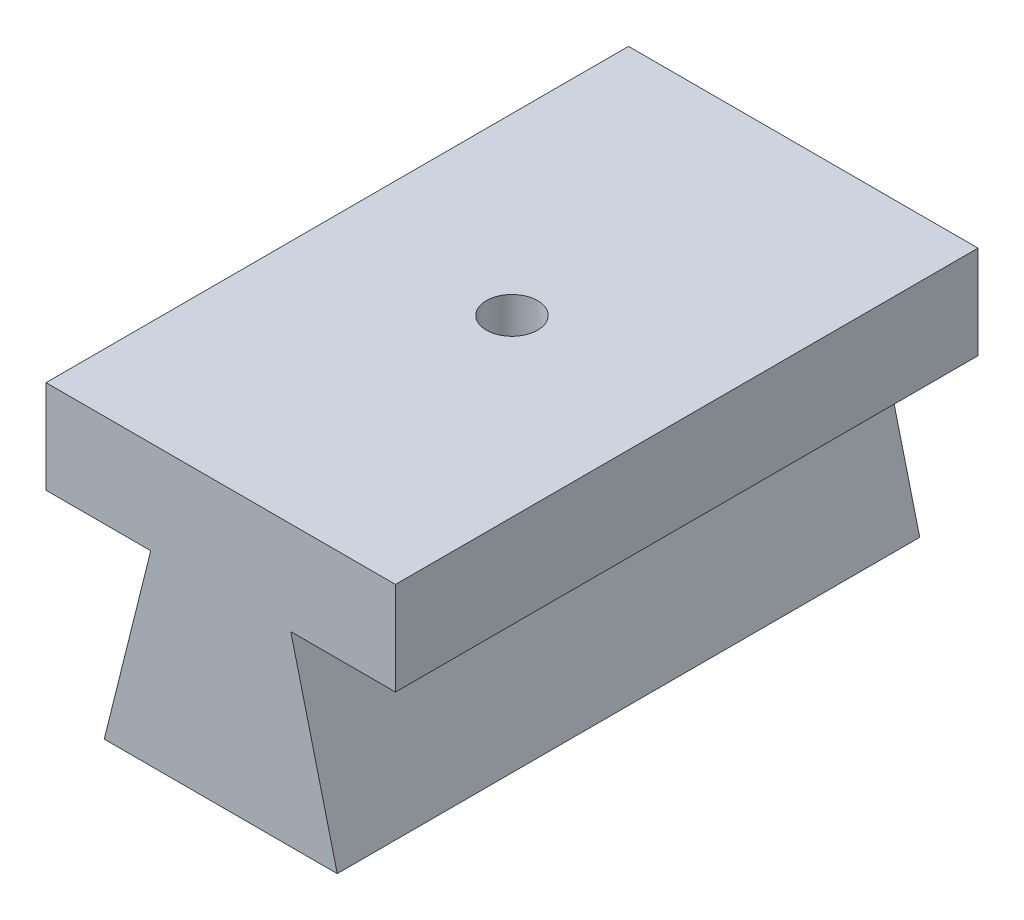
SolidWorks part; units mm, degrees
ref_plane "Front" through (0, 0, 0) normal (0, 0, 1) x (1, 0, 0)
ref_plane "Top" through (0, 0, 0) normal (0, 1, 0) x (1, 0, 0)
ref_plane "Right" through (0, 0, 0) normal (1, 0, 0) x (0, 0, -1)
sketch "Sketch1" plane through (0, 0, 0) normal (0, 0, 1) x (1, 0, 0)
  line L0 (0, 0) -> (0, 26.1543) construction
  line L1 (6.35, 0) -> (-6.35, 0)
  line L2 (-6.35, 0) -> (-3.8168, 10.16)
  line L3 (6.35, 0) -> (3.8168, 10.16)
  line L4 (-3.8168, 10.16) -> (-9.525, 10.16)
  line L5 (3.8168, 10.16) -> (9.525, 10.16)
  line L6 (-9.525, 10.16) -> (-9.525, 15.24)
  line L7 (9.525, 10.16) -> (9.525, 15.24)
  line L8 (-9.525, 15.24) -> (9.525, 15.24)
  point P5 (0, 0)
  point P13 (0, 15.24)
  dimension "D1" = 19.05
  dimension "D2" = 5.08
  dimension "D3" = 10.16
  dimension "D4" = 12.7
  dimension "D5" = 28
extrude "Base-Extrude" add sketch "Sketch1" along normal mid plane 31.75
sketch "Sketch3" plane through (0, 15.24, 0) normal (0, 1, 0) x (-1, 0, 0)
  circle A0 centre (0, 0) radius 1.397
  dimension "D1" = 2.794
extrude "Cut-Extrude2" cut sketch "Sketch3" against normal blind 12.7
sketch "Sketch4" [suppressed] plane through (0, 0, 15.875) normal (0, 0, 1) x (1, 0, 0)
  line L16 (-1.5411, 11.938) -> (-4.0743, 1.778)
  line L17 (-4.0743, 1.778) -> (4.0743, 1.778)
  line L18 (4.0743, 1.778) -> (1.5411, 11.938)
  line L19 (1.5411, 11.938) -> (7.747, 11.938)
  line L20 (7.747, 11.938) -> (7.747, 13.462)
  line L21 (7.747, 13.462) -> (-7.747, 13.462)
  line L22 (-7.747, 13.462) -> (-7.747, 11.938)
  line L23 (-7.747, 11.938) -> (-1.5411, 11.938)
  line L24 (-1.5411, 11.938) -> (-4.0743, 1.778)
  line L25 (-4.0743, 1.778) -> (4.0743, 1.778)
  line L26 (4.0743, 1.778) -> (1.5411, 11.938)
  line L27 (1.5411, 11.938) -> (7.747, 11.938)
  line L28 (7.747, 11.938) -> (7.747, 13.462)
  line L29 (7.747, 13.462) -> (-7.747, 13.462)
  line L30 (-7.747, 13.462) -> (-7.747, 11.938)
  line L31 (-7.747, 11.938) -> (-1.5411, 11.938)
  dimension "D1" = 1.778
extrude "Cut-Extrude3" [suppressed] cut sketch "Sketch4" against normal through all flip side to cut
